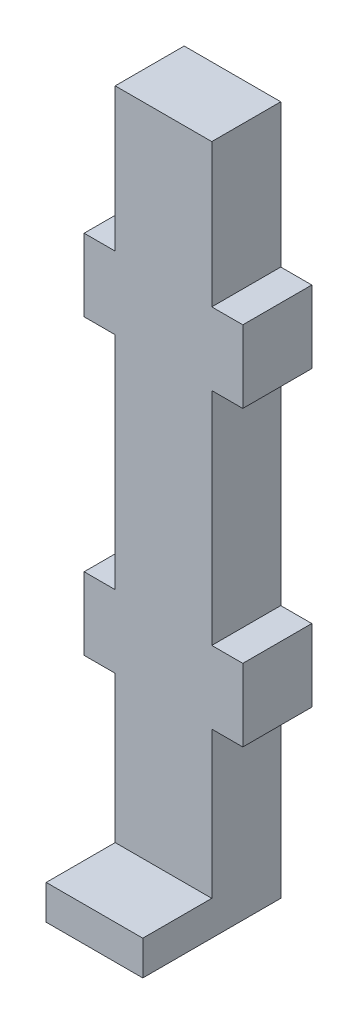
SolidWorks part; units mm, degrees
ref_plane "Front Plane" through (0, 0, 0) normal (0, 0, 1) x (1, 0, 0)
ref_plane "Top Plane" through (0, 0, 0) normal (0, 1, 0) x (1, 0, 0)
ref_plane "Right Plane" through (0, 0, 0) normal (1, 0, 0) x (0, 0, -1)
sketch "Sketch1" plane through (0, 0, 0) normal (0, 0, 1) x (1, 0, 0)
  line L1 (-2.8, -20) -> (2.8, -20)
  line L2 (-2.8, -20) -> (-2.8, 20)
  line L3 (-2.8, 20) -> (2.8, 20)
  line L4 (2.8, -20) -> (2.8, 20)
  line L5 (-2.8, -20) -> (2.8, 20) construction
  line L6 (-2.8, 20) -> (2.8, -20) construction
  point P0 (0, 0)
  dimension "D1" = 40
  dimension "D2" = 5.6
extrude "Boss-Extrude1" add sketch "Sketch1" along normal blind 4 contours L4 L3 L2 L1
sketch "Sketch2" plane through (0, 0, 4) normal (0, 0, 1) x (1, 0, 0)
  line L0 (2.8, -20) -> (2.8, 20) construction
  line L1 (-2.8, -20) -> (2.8, -20)
  line L2 (-2.8, -20) -> (-2.8, -18)
  line L3 (-2.8, -18) -> (2.8, -18)
  line L4 (2.8, -20) -> (2.8, -18)
  dimension "D1" = 2
extrude "Boss-Extrude2" add sketch "Sketch2" along normal blind 4
sketch "Sketch4" plane through (-2.8, 0, 0) normal (-1, 0, 0) x (0, 0, 1)
  line L0 (0, -20) -> (0, 20) construction
  line L1 (0, 11.7) -> (4, 11.7)
  line L2 (0, 11.7) -> (0, 7.5)
  line L3 (0, 7.5) -> (4, 7.5)
  line L4 (4, 11.7) -> (4, 7.5)
  line L5 (4, -18) -> (4, 20) construction
  line L6 (8, -20) -> (0, -20) construction
  dimension "D1" = 4.2
  dimension "D2" = 27.5
extrude "Boss-Extrude3" add sketch "Sketch4" along normal blind 1.8
ref_plane "Plane1" through (0, 0, 0) normal (-1, 0, 0) x (0, 0, 1)
mirror "Mirror1" about plane through (0, 0, 0) normal (-1, 0, 0) of "Boss-Extrude3"
sketch "Sketch6" plane through (0, 0, 4) normal (0, 0, 1) x (1, 0, 0)
  line L0 (2.8, 1.1) -> (-2.8, 1.1) construction
  line L1 (2.8, -18) -> (2.8, 7.5) construction
  line L2 (-2.8, -18) -> (-2.8, 7.5) construction
  line L3 (2.8, -18) -> (-2.8, -18) construction
  line L4 (4.6, 7.5) -> (2.8, 7.5) construction
  dimension "D1" = 19.1
  dimension "D2" = 6.4
sketch "Sketch7" plane through (-2.8, 0, 0) normal (-1, 0, 0) x (0, 0, 1)
  line L0 (4, 1.1) -> (0, 1.1) construction
  line L1 (4, -18) -> (4, 7.5) construction
  line L2 (0, -20) -> (0, 7.5) construction
  line L3 (8, -18) -> (4, -18) construction
  dimension "D1" = 19.1
ref_plane "Plane3" through (0, 1.1, 0) normal (0, -1, 0) x (-1, 0, 0)
mirror "Mirror2" about plane through (0, 1.1, 0) normal (0, -1, 0) of "Mirror1", "Boss-Extrude3"
